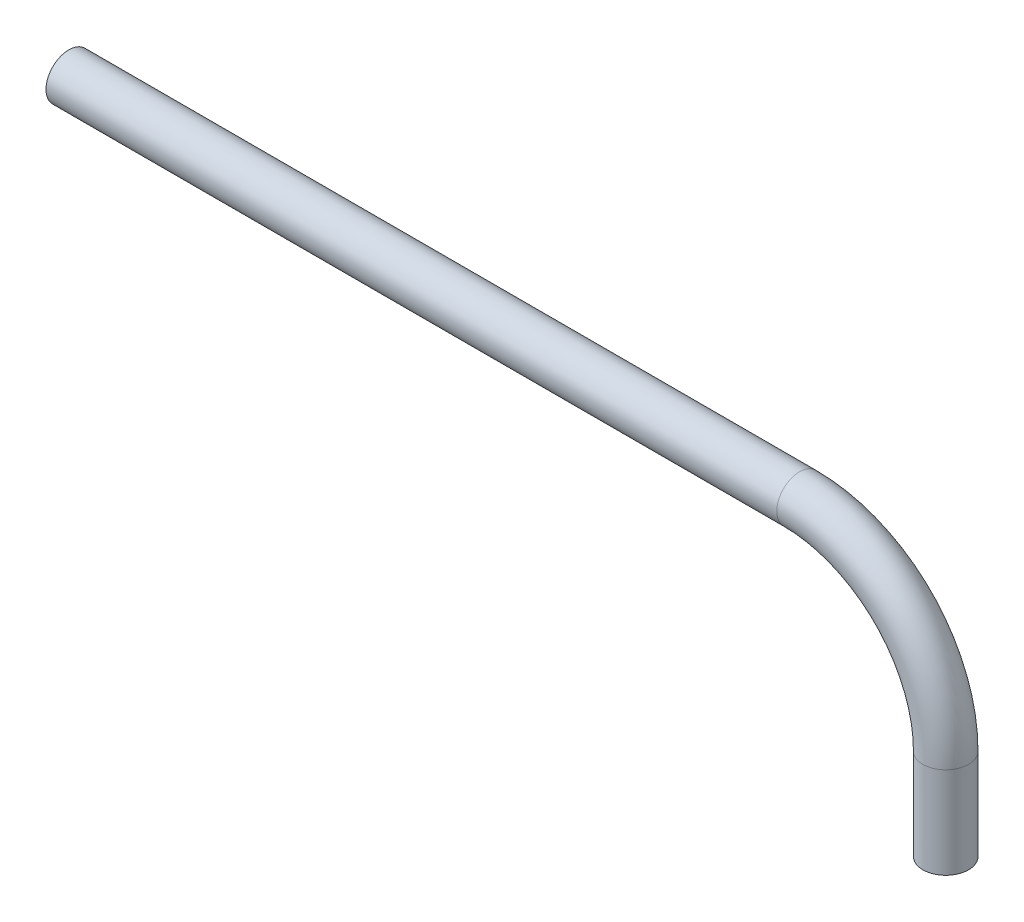
SolidWorks part; units mm, degrees
ref_plane "Front Plane" through (0, 0, 0) normal (0, 0, 1) x (1, 0, 0)
ref_plane "Top Plane" through (0, 0, 0) normal (0, 1, 0) x (1, 0, 0)
ref_plane "Right Plane" through (0, 0, 0) normal (1, 0, 0) x (0, 0, -1)
sketch "Sketch1" plane through (0, 0, 0) normal (0, 0, 1) x (1, 0, 0)
  line L0 (0, 0) -> (80, 0)
  line L1 (96, -16) -> (96, -26)
  arc A0 (80, 0) -> (96, -16) centre (80, -16) cw
  point P5 (80, -15.8102)
  dimension "D3" = 16
  dimension "D1" = 96
  dimension "D2" = 26
  dimension "D4" = 80
sweep "Sweep1" add path "Sketch1" circular profile diameter 5 parameters "D3"=5
